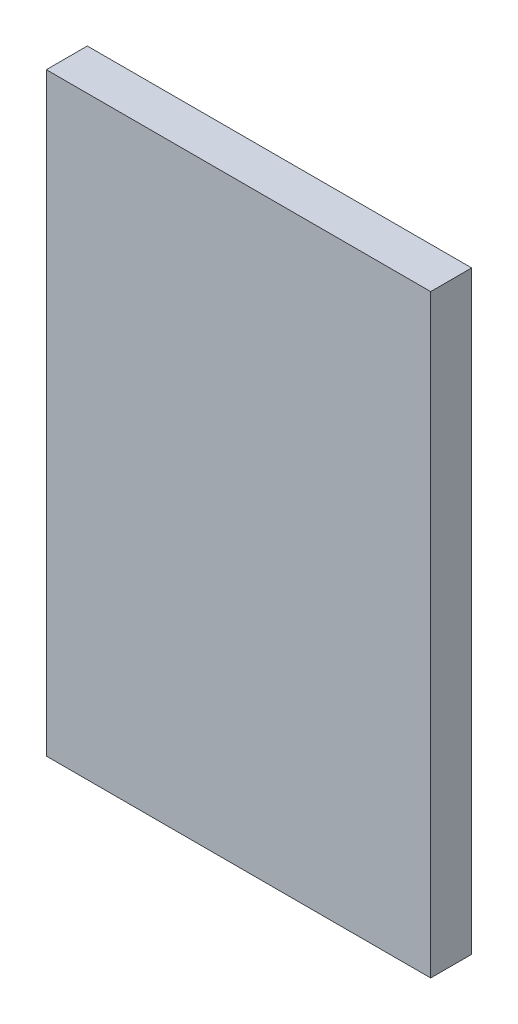
SolidWorks part; units mm, degrees
ref_plane "前视基准面" through (0, 0, 0) normal (0, 0, 1) x (1, 0, 0)
ref_plane "上视基准面" through (0, 0, 0) normal (0, 1, 0) x (1, 0, 0)
ref_plane "右视基准面" through (0, 0, 0) normal (1, 0, 0) x (0, 0, -1)
sketch "草图1" plane through (0, 0, 0) normal (0, 0, 1) x (1, 0, 0)
  line L1 (0, 0) -> (-37.5, 0)
  line L2 (0, 0) -> (0, 58)
  line L3 (0, 58) -> (-37.5, 58)
  line L4 (-37.5, 0) -> (-37.5, 58)
  dimension "D1" = 37.5
extrude "凸台-拉伸1" add sketch "草图1" along normal blind 4
